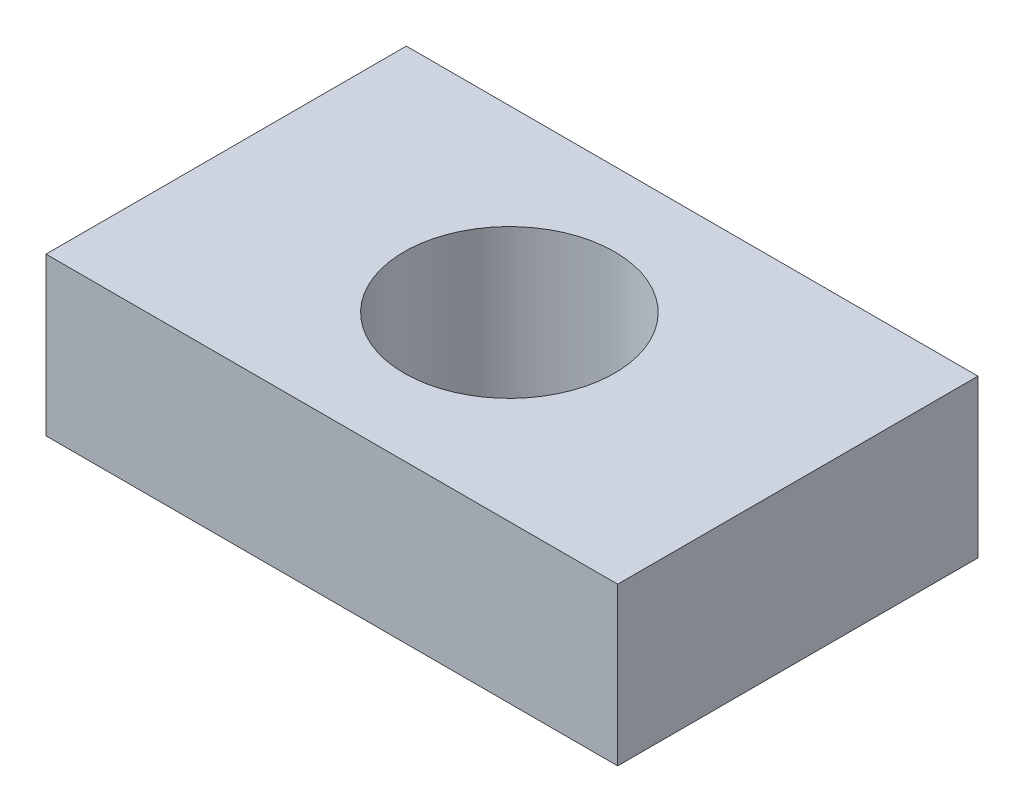
SolidWorks part; units mm, degrees
material "1060 Alloy"
ref_plane "Front Plane" through (0, 0, 0) normal (0, 0, 1) x (1, 0, 0)
ref_plane "Top Plane" through (0, 0, 0) normal (0, 1, 0) x (1, 0, 0)
ref_plane "Right Plane" through (0, 0, 0) normal (1, 0, 0) x (0, 0, -1)
sketch "Sketch1" plane through (0, 0, 0) normal (0, 1, 0) x (1, 0, 0)
  line L5 (-68.3699, 35.0872) -> (87.8182, 35.0872)
  line L6 (-68.3699, 35.0872) -> (-68.3699, -63.3574)
  line L7 (-68.3699, -63.3574) -> (87.8182, -63.3574)
  line L8 (87.8182, 35.0872) -> (87.8182, -63.3574)
  circle A0 centre (8.7335, -13.8634) radius 28.7473
extrude "Boss-Extrude2" add sketch "Sketch1" along normal blind 43
